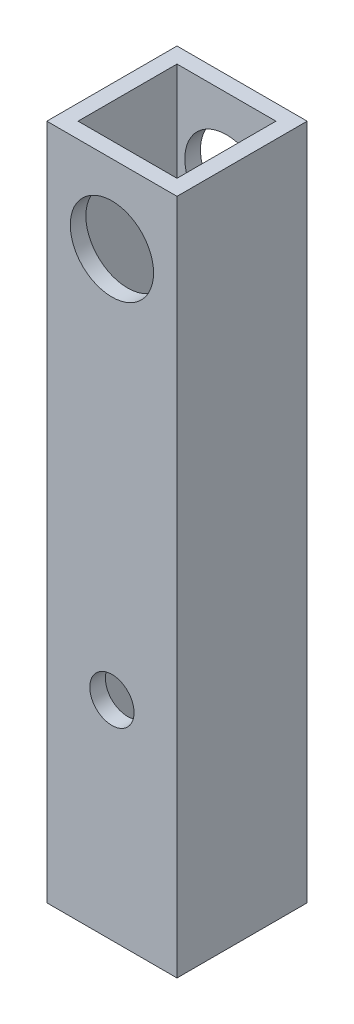
SolidWorks part; units mm, degrees
ref_plane "Front Plane" through (0, 0, 0) normal (0, 0, 1) x (1, 0, 0)
ref_plane "Top Plane" through (0, 0, 0) normal (0, 1, 0) x (1, 0, 0)
ref_plane "Right Plane" through (0, 0, 0) normal (1, 0, 0) x (0, 0, -1)
sketch "Sketch1" plane through (0, 0, 0) normal (0, 1, 0) x (1, 0, 0)
  line L1 (0, 0) -> (25, 0)
  line L2 (0, 0) -> (0, 25)
  line L3 (0, 25) -> (25, 25)
  line L4 (25, 0) -> (25, 25)
  line L5 (3, 3) -> (22, 3)
  line L6 (3, 3) -> (3, 22)
  line L7 (3, 22) -> (22, 22)
  line L8 (22, 3) -> (22, 22)
  dimension "D1" = 25
  dimension "D2" = 25
  dimension "D3" = 3
  dimension "D4" = 3
  dimension "D5" = 3
  dimension "D6" = 3
extrude "Boss-Extrude1" add sketch "Sketch1" along normal blind 130
sketch "Sketch2" plane through (0, 0, 0) normal (0, 0, 1) x (1, 0, 0)
  line L1 (25, 130) -> (25, 0) construction
  line L2 (0, 0) -> (25, 0) construction
  line L3 (0, 130) -> (25, 130) construction
  circle A0 centre (12.5, 40) radius 4.25
  circle A1 centre (12.5, 115) radius 8
  dimension "D1" = 8.5
  dimension "D2" = 16
  dimension "D3" = 12.5
  dimension "D4" = 40
  dimension "D5" = 12.5
  dimension "D6" = 15
extrude "Cut-Extrude1" cut sketch "Sketch2" against normal through all
